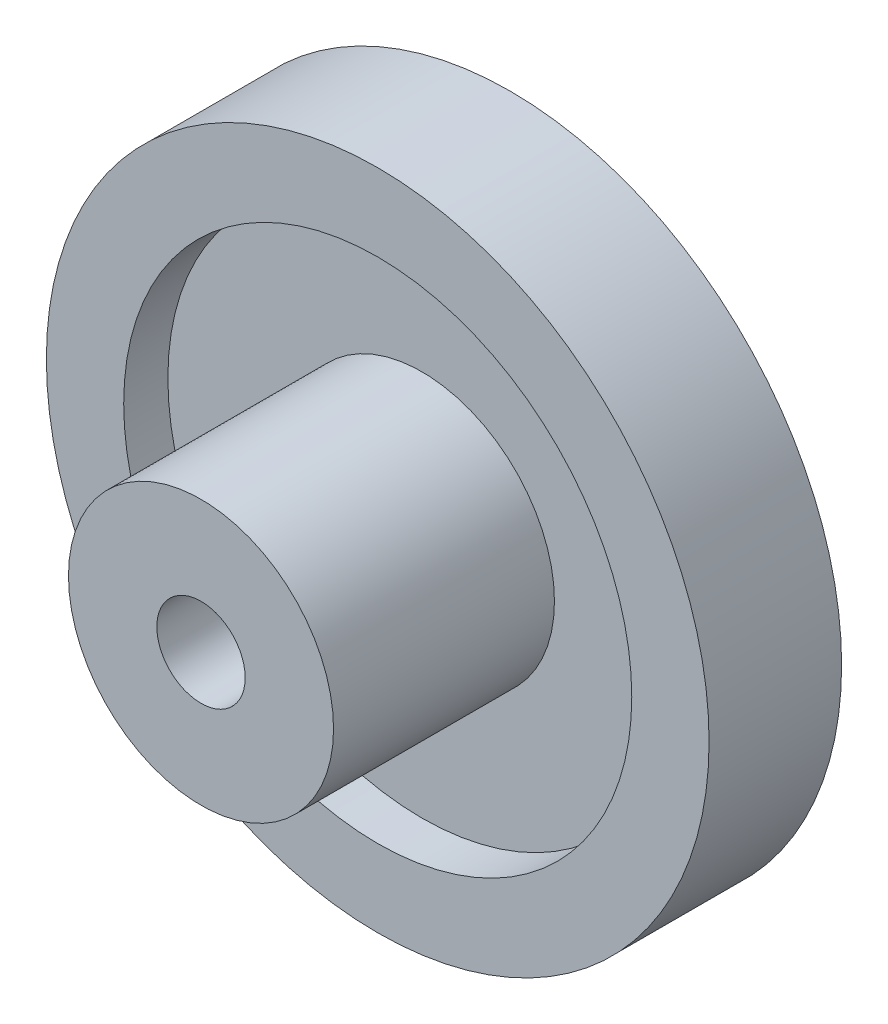
SolidWorks part; units mm, degrees
ref_plane "Plan de face" through (0, 0, 0) normal (0, 0, 1) x (1, 0, 0)
ref_plane "Plan de dessus" through (0, 0, 0) normal (0, 1, 0) x (1, 0, 0)
ref_plane "Plan de droite" through (0, 0, 0) normal (1, 0, 0) x (0, 0, -1)
sketch "Esquisse1" plane through (0, 0, 0) normal (0, 0, 1) x (1, 0, 0)
  arc A0 (7.4919, 0.3492) -> (7.4659, 0.7148) centre (0, 0) ccw
  arc A1 (7.2263, 2.0075) -> (7.1196, 2.3582) centre (0, 0) ccw
  arc A2 (6.5984, 3.5652) -> (6.4164, 3.8833) centre (0, 0) ccw
  arc A3 (5.6397, 4.9441) -> (5.3914, 5.2137) centre (0, 0) ccw
  arc A4 (4.3981, 6.0751) -> (4.0961, 6.2827) centre (0, 0) ccw
  arc A5 (2.936, 6.9014) -> (2.5953, 7.0366) centre (0, 0) ccw
  arc A6 (1.3267, 7.3817) -> (0.9645, 7.4377) centre (0, 0) ccw
  arc A7 (-0.3492, 7.4919) -> (-0.7148, 7.4659) centre (0, 0) ccw
  arc A8 (-2.0075, 7.2263) -> (-2.3582, 7.1196) centre (0, 0) ccw
  arc A9 (-3.5652, 6.5984) -> (-3.8833, 6.4164) centre (0, 0) ccw
  arc A10 (-4.9441, 5.6397) -> (-5.2137, 5.3914) centre (0, 0) ccw
  arc A11 (-6.0751, 4.3981) -> (-6.2827, 4.0961) centre (0, 0) ccw
  arc A12 (-6.9014, 2.936) -> (-7.0366, 2.5953) centre (0, 0) ccw
  arc A13 (-7.3817, 1.3267) -> (-7.4377, 0.9645) centre (0, 0) ccw
  arc A14 (-7.4919, -0.3492) -> (-7.4659, -0.7148) centre (0, 0) ccw
  arc A15 (-7.2263, -2.0075) -> (-7.1196, -2.3582) centre (0, 0) ccw
  arc A16 (-6.5984, -3.5652) -> (-6.4164, -3.8833) centre (0, 0) ccw
  arc A17 (-5.6397, -4.9441) -> (-5.3914, -5.2137) centre (0, 0) ccw
  arc A18 (-4.3981, -6.0751) -> (-4.0961, -6.2827) centre (0, 0) ccw
  arc A19 (-2.936, -6.9014) -> (-2.5953, -7.0366) centre (0, 0) ccw
  arc A20 (-1.3267, -7.3817) -> (-0.9645, -7.4377) centre (0, 0) ccw
  arc A21 (0.3492, -7.4919) -> (0.7148, -7.4659) centre (0, 0) ccw
  arc A22 (2.0075, -7.2263) -> (2.3582, -7.1196) centre (0, 0) ccw
  arc A23 (3.5652, -6.5984) -> (3.8833, -6.4164) centre (0, 0) ccw
  arc A24 (4.9441, -5.6397) -> (5.2137, -5.3914) centre (0, 0) ccw
  arc A25 (6.0751, -4.3981) -> (6.2827, -4.0961) centre (0, 0) ccw
  arc A26 (6.9014, -2.936) -> (7.0366, -2.5953) centre (0, 0) ccw
  arc A27 (7.3817, -1.3267) -> (7.4377, -0.9645) centre (0, 0) ccw
  arc A28 (6.578, 0) -> (6.372, -0.1967) centre (6.5749, -0.203) ccw
  arc A29 (6.3665, -0.3283) -> (6.5557, -0.5413) centre (6.5693, -0.3388) ccw
  arc A30 (6.3665, -0.3283) -> (6.372, -0.1967) centre (0, 0) ccw
  arc A31 (6.4131, 1.4637) -> (6.256, 1.2261) centre (6.4552, 1.2652) ccw
  arc A32 (6.28, 1.0966) -> (6.5118, 0.9311) centre (6.4799, 1.1315) ccw
  arc A33 (6.28, 1.0966) -> (6.256, 1.2261) centre (0, 0) ccw
  arc A34 (5.9266, 2.8541) -> (5.8263, 2.5875) centre (6.0118, 2.6699) ccw
  arc A35 (5.8785, 2.4666) -> (6.1413, 2.3567) centre (6.0657, 2.5451) ccw
  arc A36 (5.8785, 2.4666) -> (5.8263, 2.5875) centre (0, 0) ccw
  arc A37 (5.1429, 4.1013) -> (5.1045, 3.8191) centre (5.267, 3.9407) ccw
  arc A38 (5.1823, 3.7128) -> (5.4629, 3.6642) centre (5.3473, 3.831) ccw
  arc A39 (5.1823, 3.7128) -> (5.1045, 3.8191) centre (0, 0) ccw
  arc A40 (4.1013, 5.1429) -> (4.1267, 4.8592) centre (4.2581, 5.0139) ccw
  arc A41 (4.2261, 4.7729) -> (4.5106, 4.788) centre (4.3607, 4.9249) ccw
  arc A42 (4.2261, 4.7729) -> (4.1267, 4.8592) centre (0, 0) ccw
  arc A43 (2.8541, 5.9266) -> (2.9419, 5.6556) centre (3.0356, 5.8357) ccw
  arc A44 (3.0581, 5.5936) -> (3.3321, 5.6716) centre (3.1555, 5.7717) ccw
  arc A45 (3.0581, 5.5936) -> (2.9419, 5.6556) centre (0, 0) ccw
  arc A46 (1.4637, 6.4131) -> (1.6097, 6.1684) centre (1.6609, 6.3649) ccw
  arc A47 (1.7368, 6.1339) -> (1.9865, 6.2709) centre (1.7921, 6.3292) ccw
  arc A48 (1.7368, 6.1339) -> (1.6097, 6.1684) centre (0, 0) ccw
  arc A49 (0, 6.578) -> (0.1967, 6.372) centre (0.203, 6.5749) ccw
  arc A50 (0.3283, 6.3665) -> (0.5413, 6.5557) centre (0.3388, 6.5693) ccw
  arc A51 (0.3283, 6.3665) -> (0.1967, 6.372) centre (0, 0) ccw
  arc A52 (-1.4637, 6.4131) -> (-1.2261, 6.256) centre (-1.2652, 6.4552) ccw
  arc A53 (-1.0966, 6.28) -> (-0.9311, 6.5118) centre (-1.1315, 6.4799) ccw
  arc A54 (-1.0966, 6.28) -> (-1.2261, 6.256) centre (0, 0) ccw
  arc A55 (-2.8541, 5.9266) -> (-2.5875, 5.8263) centre (-2.6699, 6.0118) ccw
  arc A56 (-2.4666, 5.8785) -> (-2.3567, 6.1413) centre (-2.5451, 6.0657) ccw
  arc A57 (-2.4666, 5.8785) -> (-2.5875, 5.8263) centre (0, 0) ccw
  arc A58 (-4.1013, 5.1429) -> (-3.8191, 5.1045) centre (-3.9407, 5.267) ccw
  arc A59 (-3.7128, 5.1823) -> (-3.6642, 5.4629) centre (-3.831, 5.3473) ccw
  arc A60 (-3.7128, 5.1823) -> (-3.8191, 5.1045) centre (0, 0) ccw
  arc A61 (-5.1429, 4.1013) -> (-4.8592, 4.1267) centre (-5.0139, 4.2581) ccw
  arc A62 (-4.7729, 4.2261) -> (-4.788, 4.5106) centre (-4.9249, 4.3607) ccw
  arc A63 (-4.7729, 4.2261) -> (-4.8592, 4.1267) centre (0, 0) ccw
  arc A64 (-5.9266, 2.8541) -> (-5.6556, 2.9419) centre (-5.8357, 3.0356) ccw
  arc A65 (-5.5936, 3.0581) -> (-5.6716, 3.3321) centre (-5.7717, 3.1555) ccw
  arc A66 (-5.5936, 3.0581) -> (-5.6556, 2.9419) centre (0, 0) ccw
  arc A67 (-6.4131, 1.4637) -> (-6.1684, 1.6097) centre (-6.3649, 1.6609) ccw
  arc A68 (-6.1339, 1.7368) -> (-6.2709, 1.9865) centre (-6.3292, 1.7921) ccw
  arc A69 (-6.1339, 1.7368) -> (-6.1684, 1.6097) centre (0, 0) ccw
  arc A70 (-6.578, 0) -> (-6.372, 0.1967) centre (-6.5749, 0.203) ccw
  arc A71 (-6.3665, 0.3283) -> (-6.5557, 0.5413) centre (-6.5693, 0.3388) ccw
  arc A72 (-6.3665, 0.3283) -> (-6.372, 0.1967) centre (0, 0) ccw
  arc A73 (-6.4131, -1.4637) -> (-6.256, -1.2261) centre (-6.4552, -1.2652) ccw
  arc A74 (-6.28, -1.0966) -> (-6.5118, -0.9311) centre (-6.4799, -1.1315) ccw
  arc A75 (-6.28, -1.0966) -> (-6.256, -1.2261) centre (0, 0) ccw
  arc A76 (-5.9266, -2.8541) -> (-5.8263, -2.5875) centre (-6.0118, -2.6699) ccw
  arc A77 (-5.8785, -2.4666) -> (-6.1413, -2.3567) centre (-6.0657, -2.5451) ccw
  arc A78 (-5.8785, -2.4666) -> (-5.8263, -2.5875) centre (0, 0) ccw
  arc A79 (-5.1429, -4.1013) -> (-5.1045, -3.8191) centre (-5.267, -3.9407) ccw
  arc A80 (-5.1823, -3.7128) -> (-5.4629, -3.6642) centre (-5.3473, -3.831) ccw
  arc A81 (-5.1823, -3.7128) -> (-5.1045, -3.8191) centre (0, 0) ccw
  arc A82 (-4.1013, -5.1429) -> (-4.1267, -4.8592) centre (-4.2581, -5.0139) ccw
  arc A83 (-4.2261, -4.7729) -> (-4.5106, -4.788) centre (-4.3607, -4.9249) ccw
  arc A84 (-4.2261, -4.7729) -> (-4.1267, -4.8592) centre (0, 0) ccw
  arc A85 (-2.8541, -5.9266) -> (-2.9419, -5.6556) centre (-3.0356, -5.8357) ccw
  arc A86 (-3.0581, -5.5936) -> (-3.3321, -5.6716) centre (-3.1555, -5.7717) ccw
  arc A87 (-3.0581, -5.5936) -> (-2.9419, -5.6556) centre (0, 0) ccw
  arc A88 (-1.4637, -6.4131) -> (-1.6097, -6.1684) centre (-1.6609, -6.3649) ccw
  arc A89 (-1.7368, -6.1339) -> (-1.9865, -6.2709) centre (-1.7921, -6.3292) ccw
  arc A90 (-1.7368, -6.1339) -> (-1.6097, -6.1684) centre (0, 0) ccw
  arc A91 (0, -6.578) -> (-0.1967, -6.372) centre (-0.203, -6.5749) ccw
  arc A92 (-0.3283, -6.3665) -> (-0.5413, -6.5557) centre (-0.3388, -6.5693) ccw
  arc A93 (-0.3283, -6.3665) -> (-0.1967, -6.372) centre (0, 0) ccw
  arc A94 (1.4637, -6.4131) -> (1.2261, -6.256) centre (1.2652, -6.4552) ccw
  arc A95 (1.0966, -6.28) -> (0.9311, -6.5118) centre (1.1315, -6.4799) ccw
  arc A96 (1.0966, -6.28) -> (1.2261, -6.256) centre (0, 0) ccw
  arc A97 (2.8541, -5.9266) -> (2.5875, -5.8263) centre (2.6699, -6.0118) ccw
  arc A98 (2.4666, -5.8785) -> (2.3567, -6.1413) centre (2.5451, -6.0657) ccw
  arc A99 (2.4666, -5.8785) -> (2.5875, -5.8263) centre (0, 0) ccw
  arc A100 (4.1013, -5.1429) -> (3.8191, -5.1045) centre (3.9407, -5.267) ccw
  arc A101 (3.7128, -5.1823) -> (3.6642, -5.4629) centre (3.831, -5.3473) ccw
  arc A102 (3.7128, -5.1823) -> (3.8191, -5.1045) centre (0, 0) ccw
  arc A103 (5.1429, -4.1013) -> (4.8592, -4.1267) centre (5.0139, -4.2581) ccw
  arc A104 (4.7729, -4.2261) -> (4.788, -4.5106) centre (4.9249, -4.3607) ccw
  arc A105 (4.7729, -4.2261) -> (4.8592, -4.1267) centre (0, 0) ccw
  arc A106 (5.9266, -2.8541) -> (5.6556, -2.9419) centre (5.8357, -3.0356) ccw
  arc A107 (5.5936, -3.0581) -> (5.6716, -3.3321) centre (5.7717, -3.1555) ccw
  arc A108 (5.5936, -3.0581) -> (5.6556, -2.9419) centre (0, 0) ccw
  arc A109 (6.4131, -1.4637) -> (6.1684, -1.6097) centre (6.3649, -1.6609) ccw
  arc A110 (6.1339, -1.7368) -> (6.2709, -1.9865) centre (6.3292, -1.7921) ccw
  arc A111 (6.1339, -1.7368) -> (6.1684, -1.6097) centre (0, 0) ccw
  circle A112 centre (0, 0) radius 1
  spline S0 degree 3 poles (6.578, 0) (6.6119, 0) (6.7559, 0.0236) (6.9849, 0.0917) (7.2537, 0.2125) (7.4145, 0.3021) (7.4919, 0.3492) knots 0 0 0 0 0.1017 0.434977 0.714423 0.984887 0.984887 0.984887 0.984887
  spline S1 degree 3 poles (6.5118, 0.9311) (6.5453, 0.9359) (6.6912, 0.9329) (6.9276, 0.8979) (7.2108, 0.8163) (7.3826, 0.7504) (7.4659, 0.7148) knots 0 0 0 0 0.1017 0.434977 0.714423 0.984887 0.984887 0.984887 0.984887
  spline S2 degree 3 poles (6.4131, 1.4637) (6.4461, 1.4713) (6.5813, 1.5263) (6.7894, 1.6437) (7.0245, 1.8213) (7.1614, 1.9444) (7.2263, 2.0075) knots 0 0 0 0 0.1017 0.434977 0.714423 0.984887 0.984887 0.984887 0.984887
  spline S3 degree 3 poles (6.1413, 2.3567) (6.173, 2.3689) (6.3159, 2.3984) (6.5541, 2.4169) (6.8483, 2.4004) (7.0306, 2.3743) (7.1196, 2.3582) knots 0 0 0 0 0.1017 0.434977 0.714423 0.984887 0.984887 0.984887 0.984887
  spline S4 degree 3 poles (5.9266, 2.8541) (5.9571, 2.8688) (6.0766, 2.9525) (6.2534, 3.1132) (6.4431, 3.3388) (6.5492, 3.4892) (6.5984, 3.5652) knots 0 0 0 0 0.1017 0.434977 0.714423 0.984887 0.984887 0.984887 0.984887
  spline S5 degree 3 poles (5.4629, 3.6642) (5.4911, 3.6831) (5.6238, 3.7437) (5.8519, 3.8147) (6.1425, 3.8641) (6.3259, 3.8793) (6.4164, 3.8833) knots 0 0 0 0 0.1017 0.434977 0.714423 0.984887 0.984887 0.984887 0.984887
  spline S6 degree 3 poles (5.1429, 4.1013) (5.1694, 4.1225) (5.2673, 4.2307) (5.4039, 4.4267) (5.5387, 4.6888) (5.6085, 4.8591) (5.6397, 4.9441) knots 0 0 0 0 0.1017 0.434977 0.714423 0.984887 0.984887 0.984887 0.984887
  spline S7 degree 3 poles (4.5106, 4.788) (4.5339, 4.8126) (4.6498, 4.9013) (4.8563, 5.0213) (5.1286, 5.134) (5.3041, 5.1897) (5.3914, 5.2137) knots 0 0 0 0 0.1017 0.434977 0.714423 0.984887 0.984887 0.984887 0.984887
  spline S8 degree 3 poles (4.1013, 5.1429) (4.1225, 5.1694) (4.1938, 5.2967) (4.2833, 5.5182) (4.3564, 5.8037) (4.3867, 5.9853) (4.3981, 6.0751) knots 0 0 0 0 0.1017 0.434977 0.714423 0.984887 0.984887 0.984887 0.984887
  spline S9 degree 3 poles (3.3321, 5.6716) (3.3493, 5.7008) (3.4426, 5.8131) (3.6173, 5.976) (3.8576, 6.1465) (4.0163, 6.2398) (4.0961, 6.2827) knots 0 0 0 0 0.1017 0.434977 0.714423 0.984887 0.984887 0.984887 0.984887
  spline S10 degree 3 poles (2.8541, 5.9266) (2.8688, 5.9571) (2.91, 6.0971) (2.948, 6.333) (2.9558, 6.6276) (2.9448, 6.8113) (2.936, 6.9014) knots 0 0 0 0 0.1017 0.434977 0.714423 0.984887 0.984887 0.984887 0.984887
  spline S11 degree 3 poles (1.9865, 6.2709) (1.9967, 6.3032) (2.0627, 6.4334) (2.1968, 6.6311) (2.3932, 6.8508) (2.5271, 6.9771) (2.5953, 7.0366) knots 0 0 0 0 0.1017 0.434977 0.714423 0.984887 0.984887 0.984887 0.984887
  spline S12 degree 3 poles (1.4637, 6.4131) (1.4713, 6.4461) (1.4803, 6.5918) (1.4649, 6.8302) (1.4069, 7.1191) (1.3553, 7.2958) (1.3267, 7.3817) knots 0 0 0 0 0.1017 0.434977 0.714423 0.984887 0.984887 0.984887 0.984887
  spline S13 degree 3 poles (0.5413, 6.5557) (0.5441, 6.5895) (0.5794, 6.7311) (0.6661, 6.9537) (0.8087, 7.2116) (0.9112, 7.3645) (0.9645, 7.4377) knots 0 0 0 0 0.1017 0.434977 0.714423 0.984887 0.984887 0.984887 0.984887
  spline S14 degree 3 poles (0, 6.578) (0, 6.6119) (-0.0236, 6.7559) (-0.0917, 6.9849) (-0.2125, 7.2537) (-0.3021, 7.4145) (-0.3492, 7.4919) knots 0 0 0 0 0.1017 0.434977 0.714423 0.984887 0.984887 0.984887 0.984887
  spline S15 degree 3 poles (-0.9311, 6.5118) (-0.9359, 6.5453) (-0.9329, 6.6912) (-0.8979, 6.9276) (-0.8163, 7.2108) (-0.7504, 7.3826) (-0.7148, 7.4659) knots 0 0 0 0 0.1017 0.434977 0.714423 0.984887 0.984887 0.984887 0.984887
  spline S16 degree 3 poles (-1.4637, 6.4131) (-1.4713, 6.4461) (-1.5263, 6.5813) (-1.6437, 6.7894) (-1.8213, 7.0245) (-1.9444, 7.1614) (-2.0075, 7.2263) knots 0 0 0 0 0.1017 0.434977 0.714423 0.984887 0.984887 0.984887 0.984887
  spline S17 degree 3 poles (-2.3567, 6.1413) (-2.3689, 6.173) (-2.3984, 6.3159) (-2.4169, 6.5541) (-2.4004, 6.8483) (-2.3743, 7.0306) (-2.3582, 7.1196) knots 0 0 0 0 0.1017 0.434977 0.714423 0.984887 0.984887 0.984887 0.984887
  spline S18 degree 3 poles (-2.8541, 5.9266) (-2.8688, 5.9571) (-2.9525, 6.0766) (-3.1132, 6.2534) (-3.3388, 6.4431) (-3.4892, 6.5492) (-3.5652, 6.5984) knots 0 0 0 0 0.1017 0.434977 0.714423 0.984887 0.984887 0.984887 0.984887
  spline S19 degree 3 poles (-3.6642, 5.4629) (-3.6831, 5.4911) (-3.7437, 5.6238) (-3.8147, 5.8519) (-3.8641, 6.1425) (-3.8793, 6.3259) (-3.8833, 6.4164) knots 0 0 0 0 0.1017 0.434977 0.714423 0.984887 0.984887 0.984887 0.984887
  spline S20 degree 3 poles (-4.1013, 5.1429) (-4.1225, 5.1694) (-4.2307, 5.2673) (-4.4267, 5.4039) (-4.6888, 5.5387) (-4.8591, 5.6085) (-4.9441, 5.6397) knots 0 0 0 0 0.1017 0.434977 0.714423 0.984887 0.984887 0.984887 0.984887
  spline S21 degree 3 poles (-4.788, 4.5106) (-4.8126, 4.5339) (-4.9013, 4.6498) (-5.0213, 4.8563) (-5.134, 5.1286) (-5.1897, 5.3041) (-5.2137, 5.3914) knots 0 0 0 0 0.1017 0.434977 0.714423 0.984887 0.984887 0.984887 0.984887
  spline S22 degree 3 poles (-5.1429, 4.1013) (-5.1694, 4.1225) (-5.2967, 4.1938) (-5.5182, 4.2833) (-5.8037, 4.3564) (-5.9853, 4.3867) (-6.0751, 4.3981) knots 0 0 0 0 0.1017 0.434977 0.714423 0.984887 0.984887 0.984887 0.984887
  spline S23 degree 3 poles (-5.6716, 3.3321) (-5.7008, 3.3493) (-5.8131, 3.4426) (-5.976, 3.6173) (-6.1465, 3.8576) (-6.2398, 4.0163) (-6.2827, 4.0961) knots 0 0 0 0 0.1017 0.434977 0.714423 0.984887 0.984887 0.984887 0.984887
  spline S24 degree 3 poles (-5.9266, 2.8541) (-5.9571, 2.8688) (-6.0971, 2.91) (-6.333, 2.948) (-6.6276, 2.9558) (-6.8113, 2.9448) (-6.9014, 2.936) knots 0 0 0 0 0.1017 0.434977 0.714423 0.984887 0.984887 0.984887 0.984887
  spline S25 degree 3 poles (-6.2709, 1.9865) (-6.3032, 1.9967) (-6.4334, 2.0627) (-6.6311, 2.1968) (-6.8508, 2.3932) (-6.9771, 2.5271) (-7.0366, 2.5953) knots 0 0 0 0 0.1017 0.434977 0.714423 0.984887 0.984887 0.984887 0.984887
  spline S26 degree 3 poles (-6.4131, 1.4637) (-6.4461, 1.4713) (-6.5918, 1.4803) (-6.8302, 1.4649) (-7.1191, 1.4069) (-7.2958, 1.3553) (-7.3817, 1.3267) knots 0 0 0 0 0.1017 0.434977 0.714423 0.984887 0.984887 0.984887 0.984887
  spline S27 degree 3 poles (-6.5557, 0.5413) (-6.5895, 0.5441) (-6.7311, 0.5794) (-6.9537, 0.6661) (-7.2116, 0.8087) (-7.3645, 0.9112) (-7.4377, 0.9645) knots 0 0 0 0 0.1017 0.434977 0.714423 0.984887 0.984887 0.984887 0.984887
  spline S28 degree 3 poles (-6.578, 0) (-6.6119, 0) (-6.7559, -0.0236) (-6.9849, -0.0917) (-7.2537, -0.2125) (-7.4145, -0.3021) (-7.4919, -0.3492) knots 0 0 0 0 0.1017 0.434977 0.714423 0.984887 0.984887 0.984887 0.984887
  spline S29 degree 3 poles (-6.5118, -0.9311) (-6.5453, -0.9359) (-6.6912, -0.9329) (-6.9276, -0.8979) (-7.2108, -0.8163) (-7.3826, -0.7504) (-7.4659, -0.7148) knots 0 0 0 0 0.1017 0.434977 0.714423 0.984887 0.984887 0.984887 0.984887
  spline S30 degree 3 poles (-6.4131, -1.4637) (-6.4461, -1.4713) (-6.5813, -1.5263) (-6.7894, -1.6437) (-7.0245, -1.8213) (-7.1614, -1.9444) (-7.2263, -2.0075) knots 0 0 0 0 0.1017 0.434977 0.714423 0.984887 0.984887 0.984887 0.984887
  spline S31 degree 3 poles (-6.1413, -2.3567) (-6.173, -2.3689) (-6.3159, -2.3984) (-6.5541, -2.4169) (-6.8483, -2.4004) (-7.0306, -2.3743) (-7.1196, -2.3582) knots 0 0 0 0 0.1017 0.434977 0.714423 0.984887 0.984887 0.984887 0.984887
  spline S32 degree 3 poles (-5.9266, -2.8541) (-5.9571, -2.8688) (-6.0766, -2.9525) (-6.2534, -3.1132) (-6.4431, -3.3388) (-6.5492, -3.4892) (-6.5984, -3.5652) knots 0 0 0 0 0.1017 0.434977 0.714423 0.984887 0.984887 0.984887 0.984887
  spline S33 degree 3 poles (-5.4629, -3.6642) (-5.4911, -3.6831) (-5.6238, -3.7437) (-5.8519, -3.8147) (-6.1425, -3.8641) (-6.3259, -3.8793) (-6.4164, -3.8833) knots 0 0 0 0 0.1017 0.434977 0.714423 0.984887 0.984887 0.984887 0.984887
  spline S34 degree 3 poles (-5.1429, -4.1013) (-5.1694, -4.1225) (-5.2673, -4.2307) (-5.4039, -4.4267) (-5.5387, -4.6888) (-5.6085, -4.8591) (-5.6397, -4.9441) knots 0 0 0 0 0.1017 0.434977 0.714423 0.984887 0.984887 0.984887 0.984887
  spline S35 degree 3 poles (-4.5106, -4.788) (-4.5339, -4.8126) (-4.6498, -4.9013) (-4.8563, -5.0213) (-5.1286, -5.134) (-5.3041, -5.1897) (-5.3914, -5.2137) knots 0 0 0 0 0.1017 0.434977 0.714423 0.984887 0.984887 0.984887 0.984887
  spline S36 degree 3 poles (-4.1013, -5.1429) (-4.1225, -5.1694) (-4.1938, -5.2967) (-4.2833, -5.5182) (-4.3564, -5.8037) (-4.3867, -5.9853) (-4.3981, -6.0751) knots 0 0 0 0 0.1017 0.434977 0.714423 0.984887 0.984887 0.984887 0.984887
  spline S37 degree 3 poles (-3.3321, -5.6716) (-3.3493, -5.7008) (-3.4426, -5.8131) (-3.6173, -5.976) (-3.8576, -6.1465) (-4.0163, -6.2398) (-4.0961, -6.2827) knots 0 0 0 0 0.1017 0.434977 0.714423 0.984887 0.984887 0.984887 0.984887
  spline S38 degree 3 poles (-2.8541, -5.9266) (-2.8688, -5.9571) (-2.91, -6.0971) (-2.948, -6.333) (-2.9558, -6.6276) (-2.9448, -6.8113) (-2.936, -6.9014) knots 0 0 0 0 0.1017 0.434977 0.714423 0.984887 0.984887 0.984887 0.984887
  spline S39 degree 3 poles (-1.9865, -6.2709) (-1.9967, -6.3032) (-2.0627, -6.4334) (-2.1968, -6.6311) (-2.3932, -6.8508) (-2.5271, -6.9771) (-2.5953, -7.0366) knots 0 0 0 0 0.1017 0.434977 0.714423 0.984887 0.984887 0.984887 0.984887
  spline S40 degree 3 poles (-1.4637, -6.4131) (-1.4713, -6.4461) (-1.4803, -6.5918) (-1.4649, -6.8302) (-1.4069, -7.1191) (-1.3553, -7.2958) (-1.3267, -7.3817) knots 0 0 0 0 0.1017 0.434977 0.714423 0.984887 0.984887 0.984887 0.984887
  spline S41 degree 3 poles (-0.5413, -6.5557) (-0.5441, -6.5895) (-0.5794, -6.7311) (-0.6661, -6.9537) (-0.8087, -7.2116) (-0.9112, -7.3645) (-0.9645, -7.4377) knots 0 0 0 0 0.1017 0.434977 0.714423 0.984887 0.984887 0.984887 0.984887
  spline S42 degree 3 poles (0, -6.578) (0, -6.6119) (0.0236, -6.7559) (0.0917, -6.9849) (0.2125, -7.2537) (0.3021, -7.4145) (0.3492, -7.4919) knots 0 0 0 0 0.1017 0.434977 0.714423 0.984887 0.984887 0.984887 0.984887
  spline S43 degree 3 poles (0.9311, -6.5118) (0.9359, -6.5453) (0.9329, -6.6912) (0.8979, -6.9276) (0.8163, -7.2108) (0.7504, -7.3826) (0.7148, -7.4659) knots 0 0 0 0 0.1017 0.434977 0.714423 0.984887 0.984887 0.984887 0.984887
  spline S44 degree 3 poles (1.4637, -6.4131) (1.4713, -6.4461) (1.5263, -6.5813) (1.6437, -6.7894) (1.8213, -7.0245) (1.9444, -7.1614) (2.0075, -7.2263) knots 0 0 0 0 0.1017 0.434977 0.714423 0.984887 0.984887 0.984887 0.984887
  spline S45 degree 3 poles (2.3567, -6.1413) (2.3689, -6.173) (2.3984, -6.3159) (2.4169, -6.5541) (2.4004, -6.8483) (2.3743, -7.0306) (2.3582, -7.1196) knots 0 0 0 0 0.1017 0.434977 0.714423 0.984887 0.984887 0.984887 0.984887
  spline S46 degree 3 poles (2.8541, -5.9266) (2.8688, -5.9571) (2.9525, -6.0766) (3.1132, -6.2534) (3.3388, -6.4431) (3.4892, -6.5492) (3.5652, -6.5984) knots 0 0 0 0 0.1017 0.434977 0.714423 0.984887 0.984887 0.984887 0.984887
  spline S47 degree 3 poles (3.6642, -5.4629) (3.6831, -5.4911) (3.7437, -5.6238) (3.8147, -5.8519) (3.8641, -6.1425) (3.8793, -6.3259) (3.8833, -6.4164) knots 0 0 0 0 0.1017 0.434977 0.714423 0.984887 0.984887 0.984887 0.984887
  spline S48 degree 3 poles (4.1013, -5.1429) (4.1225, -5.1694) (4.2307, -5.2673) (4.4267, -5.4039) (4.6888, -5.5387) (4.8591, -5.6085) (4.9441, -5.6397) knots 0 0 0 0 0.1017 0.434977 0.714423 0.984887 0.984887 0.984887 0.984887
  spline S49 degree 3 poles (4.788, -4.5106) (4.8126, -4.5339) (4.9013, -4.6498) (5.0213, -4.8563) (5.134, -5.1286) (5.1897, -5.3041) (5.2137, -5.3914) knots 0 0 0 0 0.1017 0.434977 0.714423 0.984887 0.984887 0.984887 0.984887
  spline S50 degree 3 poles (5.1429, -4.1013) (5.1694, -4.1225) (5.2967, -4.1938) (5.5182, -4.2833) (5.8037, -4.3564) (5.9853, -4.3867) (6.0751, -4.3981) knots 0 0 0 0 0.1017 0.434977 0.714423 0.984887 0.984887 0.984887 0.984887
  spline S51 degree 3 poles (5.6716, -3.3321) (5.7008, -3.3493) (5.8131, -3.4426) (5.976, -3.6173) (6.1465, -3.8576) (6.2398, -4.0163) (6.2827, -4.0961) knots 0 0 0 0 0.1017 0.434977 0.714423 0.984887 0.984887 0.984887 0.984887
  spline S52 degree 3 poles (5.9266, -2.8541) (5.9571, -2.8688) (6.0971, -2.91) (6.333, -2.948) (6.6276, -2.9558) (6.8113, -2.9448) (6.9014, -2.936) knots 0 0 0 0 0.1017 0.434977 0.714423 0.984887 0.984887 0.984887 0.984887
  spline S53 degree 3 poles (6.2709, -1.9865) (6.3032, -1.9967) (6.4334, -2.0627) (6.6311, -2.1968) (6.8508, -2.3932) (6.9771, -2.5271) (7.0366, -2.5953) knots 0 0 0 0 0.1017 0.434977 0.714423 0.984887 0.984887 0.984887 0.984887
  spline S54 degree 3 poles (6.4131, -1.4637) (6.4461, -1.4713) (6.5918, -1.4803) (6.8302, -1.4649) (7.1191, -1.4069) (7.2958, -1.3553) (7.3817, -1.3267) knots 0 0 0 0 0.1017 0.434977 0.714423 0.984887 0.984887 0.984887 0.984887
  spline S55 degree 3 poles (6.5557, -0.5413) (6.5895, -0.5441) (6.7311, -0.5794) (6.9537, -0.6661) (7.2116, -0.8087) (7.3645, -0.9112) (7.4377, -0.9645) knots 0 0 0 0 0.1017 0.434977 0.714423 0.984887 0.984887 0.984887 0.984887
  dimension "D1" = 2
extrude "Boss.-Extru.1" add sketch "Esquisse1" along normal blind 3
sketch "Esquisse2" plane through (0, 0, 3) normal (0, 0, 1) x (1, 0, 0)
  circle A0 centre (0, 0) radius 5.75
  dimension "D1" = 11.5
extrude "Enlèv. mat.-Extru.1" cut sketch "Esquisse2" against normal blind 1
sketch "Esquisse3" plane through (0, 0, 2) normal (0, 0, 1) x (1, 0, 0)
  arc A0 (2.9773, 0.3683) -> (2.9271, 0.6573) centre (0, 0) ccw
  arc A1 (2.1922, 2.048) -> (1.9817, 2.2523) centre (0, 0) ccw
  arc A2 (0.5698, 2.9454) -> (0.2794, 2.987) centre (0, 0) ccw
  arc A3 (-1.2703, 2.7178) -> (-1.5297, 2.5807) centre (0, 0) ccw
  arc A4 (-2.6252, 1.4521) -> (-2.7544, 1.1887) centre (0, 0) ccw
  arc A5 (-2.9773, -0.3683) -> (-2.9271, -0.6573) centre (0, 0) ccw
  arc A6 (-2.1922, -2.048) -> (-1.9817, -2.2523) centre (0, 0) ccw
  arc A7 (-0.5698, -2.9454) -> (-0.2794, -2.987) centre (0, 0) ccw
  arc A8 (1.2703, -2.7178) -> (1.5297, -2.5807) centre (0, 0) ccw
  arc A9 (2.6252, -1.4521) -> (2.7544, -1.1887) centre (0, 0) ccw
  arc A10 (1.8368, -0.3764) -> (1.8687, -0.154) centre (0, 0) ccw
  arc A11 (1.7073, 0.7751) -> (1.6023, 0.9738) centre (0, 0) ccw
  arc A12 (0.9256, 1.6306) -> (0.7239, 1.7296) centre (0, 0) ccw
  arc A13 (-0.2096, 1.8632) -> (-0.431, 1.8248) centre (0, 0) ccw
  arc A14 (-1.2648, 1.3842) -> (-1.4213, 1.2229) centre (0, 0) ccw
  arc A15 (-1.8368, 0.3764) -> (-1.8687, 0.154) centre (0, 0) ccw
  arc A16 (-1.7073, -0.7751) -> (-1.6023, -0.9738) centre (0, 0) ccw
  arc A17 (-0.9256, -1.6306) -> (-0.7239, -1.7296) centre (0, 0) ccw
  arc A18 (0.2096, -1.8632) -> (0.431, -1.8248) centre (0, 0) ccw
  arc A19 (1.2648, -1.3842) -> (1.4213, -1.2229) centre (0, 0) ccw
  circle A20 centre (0, 0) radius 1 construction
  circle A21 centre (0, 0) radius 1
  spline S0 degree 3 poles (2.349, 0) (2.3611, 0) (2.4126, 0.0085) (2.4945, 0.0326) (2.6584, 0.1065) (2.823, 0.2207) (2.9394, 0.3292) (2.9773, 0.3683) knots 0 0 0 0 0.036251 0.155621 0.255291 0.575255 0.744085 0.744085 0.744085 0.744085
  spline S1 degree 3 poles (2.2114, 0.7921) (2.2228, 0.7962) (2.2741, 0.8056) (2.3594, 0.8105) (2.5386, 0.7962) (2.7321, 0.7442) (2.8782, 0.6813) (2.9271, 0.6573) knots 0 0 0 0 0.036251 0.155621 0.255291 0.575255 0.744085 0.744085 0.744085 0.744085
  spline S2 degree 3 poles (1.9004, 1.3807) (1.9102, 1.3878) (1.9469, 1.4249) (1.9989, 1.4926) (2.0881, 1.6487) (2.1541, 1.8379) (2.1845, 1.9941) (2.1922, 2.048) knots 0 0 0 0 0.036251 0.155621 0.255291 0.575255 0.744085 0.744085 0.744085 0.744085
  spline S3 degree 3 poles (1.3235, 1.9407) (1.3303, 1.9507) (1.3663, 1.9885) (1.4324, 2.0425) (1.5858, 2.1363) (1.7728, 2.2079) (1.9281, 2.243) (1.9817, 2.2523) knots 0 0 0 0 0.036251 0.155621 0.255291 0.575255 0.744085 0.744085 0.744085 0.744085
  spline S4 degree 3 poles (0.7259, 2.234) (0.7296, 2.2455) (0.7375, 2.2971) (0.7398, 2.3825) (0.7202, 2.5612) (0.6625, 2.753) (0.5952, 2.8973) (0.5698, 2.9454) knots 0 0 0 0 0.036251 0.155621 0.255291 0.575255 0.744085 0.744085 0.744085 0.744085
  spline S5 degree 3 poles (-0.07, 2.348) (-0.0704, 2.36) (-0.0634, 2.4118) (-0.0417, 2.4943) (0.0272, 2.6604) (0.1365, 2.8283) (0.2415, 2.9479) (0.2794, 2.987) knots 0 0 0 0 0.036251 0.155621 0.255291 0.575255 0.744085 0.744085 0.744085 0.744085
  spline S6 degree 3 poles (-0.7259, 2.234) (-0.7296, 2.2455) (-0.7536, 2.2919) (-0.8019, 2.3623) (-0.9228, 2.4954) (-1.0823, 2.6166) (-1.2215, 2.6938) (-1.2703, 2.7178) knots 0 0 0 0 0.036251 0.155621 0.255291 0.575255 0.744085 0.744085 0.744085 0.744085
  spline S7 degree 3 poles (-1.4367, 1.8584) (-1.4441, 1.8679) (-1.4689, 1.9139) (-1.4999, 1.9934) (-1.5417, 2.1683) (-1.552, 2.3684) (-1.5374, 2.5268) (-1.5297, 2.5807) knots 0 0 0 0 0.036251 0.155621 0.255291 0.575255 0.744085 0.744085 0.744085 0.744085
  spline S8 degree 3 poles (-1.9004, 1.3807) (-1.9102, 1.3878) (-1.9568, 1.4112) (-2.0373, 1.4398) (-2.2133, 1.4764) (-2.4136, 1.4808) (-2.5715, 1.4614) (-2.6252, 1.4521) knots 0 0 0 0 0.036251 0.155621 0.255291 0.575255 0.744085 0.744085 0.744085 0.744085
  spline S9 degree 3 poles (-2.2547, 0.659) (-2.2663, 0.6624) (-2.3133, 0.6849) (-2.3852, 0.7311) (-2.5218, 0.848) (-2.6477, 1.0038) (-2.729, 1.1406) (-2.7544, 1.1887) knots 0 0 0 0 0.036251 0.155621 0.255291 0.575255 0.744085 0.744085 0.744085 0.744085
  spline S10 degree 3 poles (-2.349, 0) (-2.3611, 0) (-2.4126, -0.0085) (-2.4945, -0.0326) (-2.6584, -0.1065) (-2.823, -0.2207) (-2.9394, -0.3292) (-2.9773, -0.3683) knots 0 0 0 0 0.036251 0.155621 0.255291 0.575255 0.744085 0.744085 0.744085 0.744085
  spline S11 degree 3 poles (-2.2114, -0.7921) (-2.2228, -0.7962) (-2.2741, -0.8056) (-2.3594, -0.8105) (-2.5386, -0.7962) (-2.7321, -0.7442) (-2.8782, -0.6813) (-2.9271, -0.6573) knots 0 0 0 0 0.036251 0.155621 0.255291 0.575255 0.744085 0.744085 0.744085 0.744085
  spline S12 degree 3 poles (-1.9004, -1.3807) (-1.9102, -1.3878) (-1.9469, -1.4249) (-1.9989, -1.4926) (-2.0881, -1.6487) (-2.1541, -1.8379) (-2.1845, -1.9941) (-2.1922, -2.048) knots 0 0 0 0 0.036251 0.155621 0.255291 0.575255 0.744085 0.744085 0.744085 0.744085
  spline S13 degree 3 poles (-1.3235, -1.9407) (-1.3303, -1.9507) (-1.3663, -1.9885) (-1.4324, -2.0425) (-1.5858, -2.1363) (-1.7728, -2.2079) (-1.9281, -2.243) (-1.9817, -2.2523) knots 0 0 0 0 0.036251 0.155621 0.255291 0.575255 0.744085 0.744085 0.744085 0.744085
  spline S14 degree 3 poles (-0.7259, -2.234) (-0.7296, -2.2455) (-0.7375, -2.2971) (-0.7398, -2.3825) (-0.7202, -2.5612) (-0.6625, -2.753) (-0.5952, -2.8973) (-0.5698, -2.9454) knots 0 0 0 0 0.036251 0.155621 0.255291 0.575255 0.744085 0.744085 0.744085 0.744085
  spline S15 degree 3 poles (0.07, -2.348) (0.0704, -2.36) (0.0634, -2.4118) (0.0417, -2.4943) (-0.0272, -2.6604) (-0.1365, -2.8283) (-0.2415, -2.9479) (-0.2794, -2.987) knots 0 0 0 0 0.036251 0.155621 0.255291 0.575255 0.744085 0.744085 0.744085 0.744085
  spline S16 degree 3 poles (0.7259, -2.234) (0.7296, -2.2455) (0.7536, -2.2919) (0.8019, -2.3623) (0.9228, -2.4954) (1.0823, -2.6166) (1.2215, -2.6938) (1.2703, -2.7178) knots 0 0 0 0 0.036251 0.155621 0.255291 0.575255 0.744085 0.744085 0.744085 0.744085
  spline S17 degree 3 poles (1.4367, -1.8584) (1.4441, -1.8679) (1.4689, -1.9139) (1.4999, -1.9934) (1.5417, -2.1683) (1.552, -2.3684) (1.5374, -2.5268) (1.5297, -2.5807) knots 0 0 0 0 0.036251 0.155621 0.255291 0.575255 0.744085 0.744085 0.744085 0.744085
  spline S18 degree 3 poles (1.9004, -1.3807) (1.9102, -1.3878) (1.9568, -1.4112) (2.0373, -1.4398) (2.2133, -1.4764) (2.4136, -1.4808) (2.5715, -1.4614) (2.6252, -1.4521) knots 0 0 0 0 0.036251 0.155621 0.255291 0.575255 0.744085 0.744085 0.744085 0.744085
  spline S19 degree 3 poles (2.2547, -0.659) (2.2663, -0.6624) (2.3133, -0.6849) (2.3852, -0.7311) (2.5218, -0.848) (2.6477, -1.0038) (2.729, -1.1406) (2.7544, -1.1887) knots 0 0 0 0 0.036251 0.155621 0.255291 0.575255 0.744085 0.744085 0.744085 0.744085
  spline S20 degree 3 poles (2.349, 0) (2.2648, 0) (2.1034, 0.0291) (1.8817, -0.0633) (1.8687, -0.154) knots 0 0 0 0 0.252618 0.527509 0.527509 0.527509 0.527509
  spline S21 degree 3 poles (2.2547, -0.659) (2.1739, -0.6353) (2.0108, -0.618) (1.8238, -0.4671) (1.8368, -0.3764) knots 0 0 0 0 0.252618 0.527509 0.527509 0.527509 0.527509
  spline S22 degree 3 poles (1.9004, 1.3807) (1.8323, 1.3312) (1.6846, 1.2599) (1.5595, 1.0548) (1.6023, 0.9738) knots 0 0 0 0 0.252618 0.527509 0.527509 0.527509 0.527509
  spline S23 degree 3 poles (2.2114, 0.7921) (2.1321, 0.7637) (1.99, 0.682) (1.7501, 0.6941) (1.7073, 0.7751) knots 0 0 0 0 0.252618 0.527509 0.527509 0.527509 0.527509
  spline S24 degree 3 poles (0.7259, 2.234) (0.6999, 2.1539) (0.6223, 2.0095) (0.6416, 1.77) (0.7239, 1.7296) knots 0 0 0 0 0.252618 0.527509 0.527509 0.527509 0.527509
  spline S25 degree 3 poles (1.3235, 1.9407) (1.276, 1.8711) (1.2091, 1.7214) (1.0079, 1.5902) (0.9256, 1.6306) knots 0 0 0 0 0.252618 0.527509 0.527509 0.527509 0.527509
  spline S26 degree 3 poles (-0.7259, 2.234) (-0.6999, 2.1539) (-0.6776, 1.9915) (-0.5213, 1.8091) (-0.431, 1.8248) knots 0 0 0 0 0.252618 0.527509 0.527509 0.527509 0.527509
  spline S27 degree 3 poles (-0.07, 2.348) (-0.0675, 2.2638) (-0.0336, 2.1034) (-0.1193, 1.8789) (-0.2096, 1.8632) knots 0 0 0 0 0.252618 0.527509 0.527509 0.527509 0.527509
  spline S28 degree 3 poles (-1.9004, 1.3807) (-1.8323, 1.3312) (-1.7188, 1.2128) (-1.4851, 1.1572) (-1.4213, 1.2229) knots 0 0 0 0 0.252618 0.527509 0.527509 0.527509 0.527509
  spline S29 degree 3 poles (-1.4367, 1.8584) (-1.3852, 1.7918) (-1.2635, 1.6819) (-1.2009, 1.4499) (-1.2648, 1.3842) knots 0 0 0 0 0.252618 0.527509 0.527509 0.527509 0.527509
  spline S30 degree 3 poles (-2.349, 0) (-2.2648, 0) (-2.1034, -0.0291) (-1.8817, 0.0633) (-1.8687, 0.154) knots 0 0 0 0 0.252618 0.527509 0.527509 0.527509 0.527509
  spline S31 degree 3 poles (-2.2547, 0.659) (-2.1739, 0.6353) (-2.0108, 0.618) (-1.8238, 0.4671) (-1.8368, 0.3764) knots 0 0 0 0 0.252618 0.527509 0.527509 0.527509 0.527509
  spline S32 degree 3 poles (-1.9004, -1.3807) (-1.8323, -1.3312) (-1.6846, -1.2599) (-1.5595, -1.0548) (-1.6023, -0.9738) knots 0 0 0 0 0.252618 0.527509 0.527509 0.527509 0.527509
  spline S33 degree 3 poles (-2.2114, -0.7921) (-2.1321, -0.7637) (-1.99, -0.682) (-1.7501, -0.6941) (-1.7073, -0.7751) knots 0 0 0 0 0.252618 0.527509 0.527509 0.527509 0.527509
  spline S34 degree 3 poles (-0.7259, -2.234) (-0.6999, -2.1539) (-0.6223, -2.0095) (-0.6416, -1.77) (-0.7239, -1.7296) knots 0 0 0 0 0.252618 0.527509 0.527509 0.527509 0.527509
  spline S35 degree 3 poles (-1.3235, -1.9407) (-1.276, -1.8711) (-1.2091, -1.7214) (-1.0079, -1.5902) (-0.9256, -1.6306) knots 0 0 0 0 0.252618 0.527509 0.527509 0.527509 0.527509
  spline S36 degree 3 poles (0.7259, -2.234) (0.6999, -2.1539) (0.6776, -1.9915) (0.5213, -1.8091) (0.431, -1.8248) knots 0 0 0 0 0.252618 0.527509 0.527509 0.527509 0.527509
  spline S37 degree 3 poles (0.07, -2.348) (0.0675, -2.2638) (0.0336, -2.1034) (0.1193, -1.8789) (0.2096, -1.8632) knots 0 0 0 0 0.252618 0.527509 0.527509 0.527509 0.527509
  spline S38 degree 3 poles (1.9004, -1.3807) (1.8323, -1.3312) (1.7188, -1.2128) (1.4851, -1.1572) (1.4213, -1.2229) knots 0 0 0 0 0.252618 0.527509 0.527509 0.527509 0.527509
  spline S39 degree 3 poles (1.4367, -1.8584) (1.3852, -1.7918) (1.2635, -1.6819) (1.2009, -1.4499) (1.2648, -1.3842) knots 0 0 0 0 0.252618 0.527509 0.527509 0.527509 0.527509
extrude "Boss.-Extru.2" add sketch "Esquisse3" along normal blind 5
sketch "Esquisse4" plane through (0, 0, 3) normal (0, 0, 1) x (1, 0, 0)
  circle A0 centre (0, 0) radius 5.75
  circle A1 centre (0, 0) radius 7.5
extrude "Boss.-Extru.3" add sketch "Esquisse4" against normal up to surface (3 mm away) up to face at (0, 0, 0)
sketch "Esquisse5" plane through (0, 0, 7) normal (0, 0, 1) x (1, 0, 0)
  circle A0 centre (0, 0) radius 3
  circle A1 centre (0, 0) radius 1
extrude "Boss.-Extru.4" add sketch "Esquisse5" against normal up to surface (5 mm away) up to face at (5.75, 0, 2)
